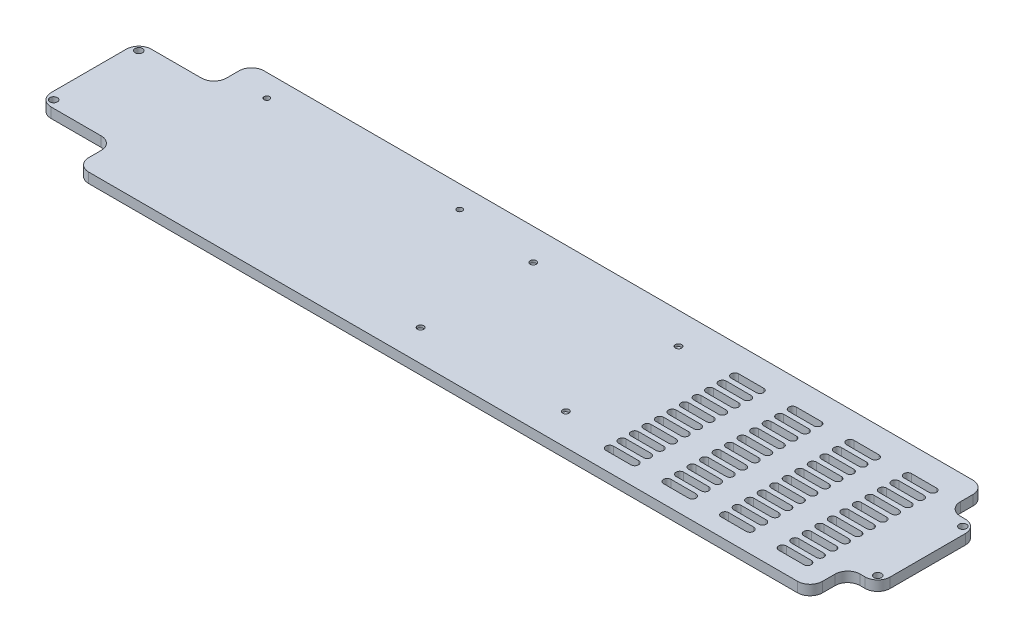
SolidWorks part; units mm, degrees
ref_plane "Plane Front" through (0, 0, 0) normal (0, 0, 1) x (1, 0, 0)
ref_plane "Plane Top" through (0, 0, 0) normal (0, 1, 0) x (1, 0, 0)
ref_plane "Plane Right" through (0, 0, 0) normal (1, 0, 0) x (0, 0, -1)
sketch "Sketch1" plane through (0, 0, 0) normal (0, 1, 0) x (1, 0, 0)
  line L1 (-154.8529, 38.7266) -> (180.1471, 38.7266)
  line L2 (-154.8529, 38.7266) -> (-154.8529, -31.2734)
  line L3 (-154.8529, -31.2734) -> (180.1471, -31.2734)
  line L4 (180.1471, 38.7266) -> (180.1471, -31.2734)
  dimension "D1" = 70
  dimension "D2" = 335
extrude "Extrude1" add sketch "Sketch1" along normal blind 4
sketch "Sketch2" plane through (0, 4, 0) normal (0, 1, 0) x (1, 0, 0)
  line L1 (-154.8529, 38.7266) -> (-124.8529, 38.7266)
  line L2 (-154.8529, 38.7266) -> (-154.8529, 23.7266)
  line L3 (-154.8529, 23.7266) -> (-124.8529, 23.7266)
  line L4 (-124.8529, 38.7266) -> (-124.8529, 23.7266)
  line L9 (-154.8529, -31.2734) -> (-124.8529, -31.2734)
  line L10 (-154.8529, -31.2734) -> (-154.8529, -16.2734)
  line L11 (-154.8529, -16.2734) -> (-124.8529, -16.2734)
  line L12 (-124.8529, -31.2734) -> (-124.8529, -16.2734)
  line L13 (180.1471, 38.7266) -> (168.1471, 38.7266)
  line L14 (180.1471, 38.7266) -> (180.1471, 23.7266)
  line L15 (180.1471, 23.7266) -> (168.1471, 23.7266)
  line L16 (168.1471, 38.7266) -> (168.1471, 23.7266)
  line L17 (180.1471, -31.2734) -> (168.1471, -31.2734)
  line L18 (180.1471, -31.2734) -> (180.1471, -16.2734)
  line L19 (180.1471, -16.2734) -> (168.1471, -16.2734)
  line L20 (168.1471, -31.2734) -> (168.1471, -16.2734)
  dimension "D1" = 15
  dimension "D2" = 30
  dimension "D3" = 15
  dimension "D4" = 30
  dimension "D5" = 15
  dimension "D6" = 15
  dimension "D7" = 12
  dimension "D8" = 12
extrude "Extrude2" cut sketch "Sketch2" against normal through all
sketch "Sketch3" plane through (0, 4, 0) normal (0, 1, 0) x (1, 0, 0)
  line L0 (168.1471, 38.7266) -> (-124.8529, 38.7266) construction
  line L1 (-114.8529, 34.8266) -> (-27.8529, 34.8266)
  line L2 (-114.8529, 34.8266) -> (-114.8529, -27.3734)
  line L3 (-114.8529, -27.3734) -> (-27.8529, -27.3734)
  line L4 (-27.8529, 34.8266) -> (-27.8529, -27.3734)
  line L5 (-124.8529, -31.2734) -> (168.1471, -31.2734) construction
  line L6 (-124.8529, 23.7266) -> (-124.8529, 38.7266) construction
  point P4 (-71.3529, 34.8266)
  point P7 (-71.3529, -27.3734)
  dimension "D1" = 62.2
  dimension "D2" = 3.9
  dimension "D3" = 3.9
  dimension "D4" = 10
  dimension "D5" = 87
sketch "Sketch4" plane through (0, 4, 0) normal (0, 1, 0) x (1, 0, 0)
  line L0 (-114.8529, 34.8266) -> (-27.8529, 34.8266) construction
  line L1 (-27.8529, 34.8266) -> (-27.8529, -27.3734) construction
  line L2 (-114.8529, 34.8266) -> (-114.8529, -27.3734) construction
  circle A0 centre (-109.8529, 29.8266) radius 1.1
  circle A1 centre (-32.8529, 29.8266) radius 1.1
  dimension "D1" = 2.2
  dimension "D2" = 2.2
  dimension "D3" = 5
  dimension "D4" = 5
  dimension "D5" = 5
  dimension "D6" = 5
extrude "Extrude4" cut sketch "Sketch4" against normal through all
sketch "Sketch5" plane through (0, 4, 0) normal (0, 1, 0) x (1, 0, 0)
  line L0 (168.1471, 38.7266) -> (-124.8529, 38.7266) construction
  line L1 (-124.8529, -31.2734) -> (168.1471, -31.2734) construction
  line L2 (-124.8529, -31.2734) -> (-124.8529, -16.2734) construction
  line L3 (-124.8529, 23.7266) -> (-124.8529, 38.7266) construction
  circle A0 centre (0.1471, 26.2266) radius 1.25
  circle A1 centre (0.1471, -18.7734) radius 1.25
  circle A2 centre (58.1471, 26.2266) radius 1.25
  circle A3 centre (58.1471, -18.7734) radius 1.25
  dimension "D1" = 12.5
  dimension "D2" = 2.5
  dimension "D4" = 2.5
  dimension "D5" = 125
  dimension "D7" = 58
  dimension "D8" = 2.5
  dimension "D9" = 2.5
  dimension "D3" = 12.5
  dimension "D6" = 125
extrude "Extrude5" cut sketch "Sketch5" against normal blind 1
sketch "Sketch6" plane through (0, 4, 0) normal (0, 1, 0) x (1, 0, 0)
  line L0 (148.6471, -22.7734) -> (158.6471, -22.7734) construction
  line L1 (148.6471, -21.2734) -> (158.6471, -21.2734)
  line L2 (148.6471, -24.2734) -> (158.6471, -24.2734)
  line L3 (168.1471, -16.2734) -> (168.1471, -31.2734) construction
  line L4 (-124.8529, -31.2734) -> (168.1471, -31.2734) construction
  arc A0 (148.6471, -21.2734) -> (148.6471, -24.2734) centre (148.6471, -22.7734) ccw
  arc A1 (158.6471, -24.2734) -> (158.6471, -21.2734) centre (158.6471, -22.7734) ccw
  point P2 (153.6471, -22.7734)
  point P7 (160.1471, -22.7734)
  point P8 (147.1471, -22.7734)
  point P9 (153.6471, -24.2734)
  point P10 (0, 0)
  point P11 (0, 0)
  dimension "D1" = 13
  dimension "D2" = 3
  dimension "D3" = 8
  dimension "D4" = 7
extrude "Extrude6" cut sketch "Sketch6" against normal through all
pattern_linear "LPattern1" count 11 spacing 5 along (0, 0, -1) count 4 spacing 23 along (-1, 0, 0) of "Extrude6"
fillet "Fillet1" radius 5 12 edges at (168.1471, 2, 31.2734) (168.1471, 2, 16.2734) (180.1471, 2, 16.2734) (180.1471, 2, -23.7266) (168.1471, 2, -23.7266) (168.1471, 2, -38.7266) (-124.8529, 2, -38.7266) (-124.8529, 2, -23.7266) (-154.8529, 2, -23.7266) (-124.8529, 2, 31.2734) (-124.8529, 2, 16.2734) (-154.8529, 2, 16.2734)
sketch "Sketch7" plane through (0, 4, 0) normal (0, 1, 0) x (1, 0, 0)
  line L0 (-149.8529, 23.7266) -> (-129.8529, 23.7266) construction
  line L1 (-154.8529, 18.7266) -> (-154.8529, -11.2734) construction
  line L2 (-129.8529, -16.2734) -> (-149.8529, -16.2734) construction
  line L3 (180.1471, -11.2734) -> (180.1471, 18.7266) construction
  line L4 (175.1471, -16.2734) -> (173.1471, -16.2734) construction
  line L5 (173.1471, 23.7266) -> (175.1471, 23.7266) construction
  circle A0 centre (-151.8529, 20.7266) radius 1.5
  circle A1 centre (-151.8529, -13.2734) radius 1.5
  circle A2 centre (177.1471, -13.2734) radius 1.5
  circle A3 centre (177.1471, 20.7266) radius 1.5
  point P10 (0, 0)
  point P12 (-152.7275, 35.7437)
  point P16 (-148.3618, -11.3077)
  dimension "D1" = 3
  dimension "D2" = 3
  dimension "D3" = 3
  dimension "D4" = 3
  dimension "D5" = 3
  dimension "D6" = 3
  dimension "D7" = 3
  dimension "D8" = 3
  dimension "D9" = 3
  dimension "D10" = 3
  dimension "D11" = 3
  dimension "D12" = 3
extrude "Extrude7" cut sketch "Sketch7" against normal through all
